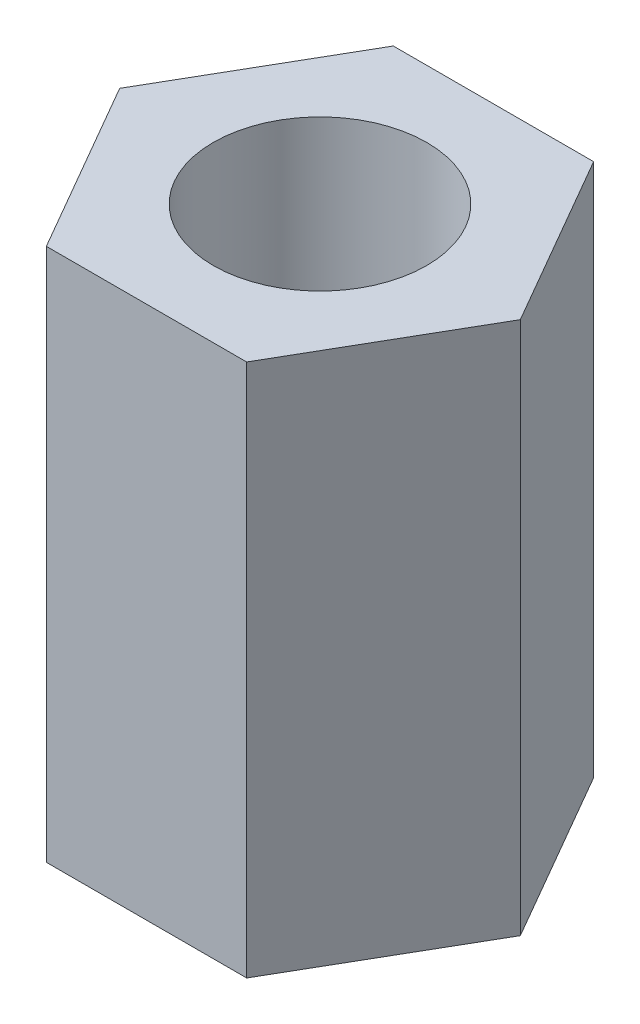
SolidWorks part; units mm, degrees
ref_plane "Front Plane" through (0, 0, 0) normal (0, 0, 1) x (1, 0, 0)
ref_plane "Top Plane" through (0, 0, 0) normal (0, 1, 0) x (1, 0, 0)
ref_plane "Right Plane" through (0, 0, 0) normal (1, 0, 0) x (0, 0, -1)
sketch "Sketch1" plane through (0, 0, 0) normal (0, 1, 0) x (1, 0, 0)
  line L0 (0, 6.5039) -> (0, 0) construction
  line L1 (3.755, 6.5039) -> (-3.755, 6.5039)
  line L2 (-3.755, 6.5039) -> (-7.51, 0)
  line L3 (-7.51, 0) -> (-3.755, -6.5039)
  line L4 (-3.755, -6.5039) -> (3.755, -6.5039)
  line L5 (3.755, -6.5039) -> (7.51, 0)
  line L6 (7.51, 0) -> (3.755, 6.5039)
  circle A0 centre (0, 0) radius 6.5039 construction
  circle A1 centre (0, 0) radius 4
  dimension "D2" = 8
  dimension "D1" = 7.51
extrude "Boss-Extrude1" add sketch "Sketch1" along normal mid plane 20
